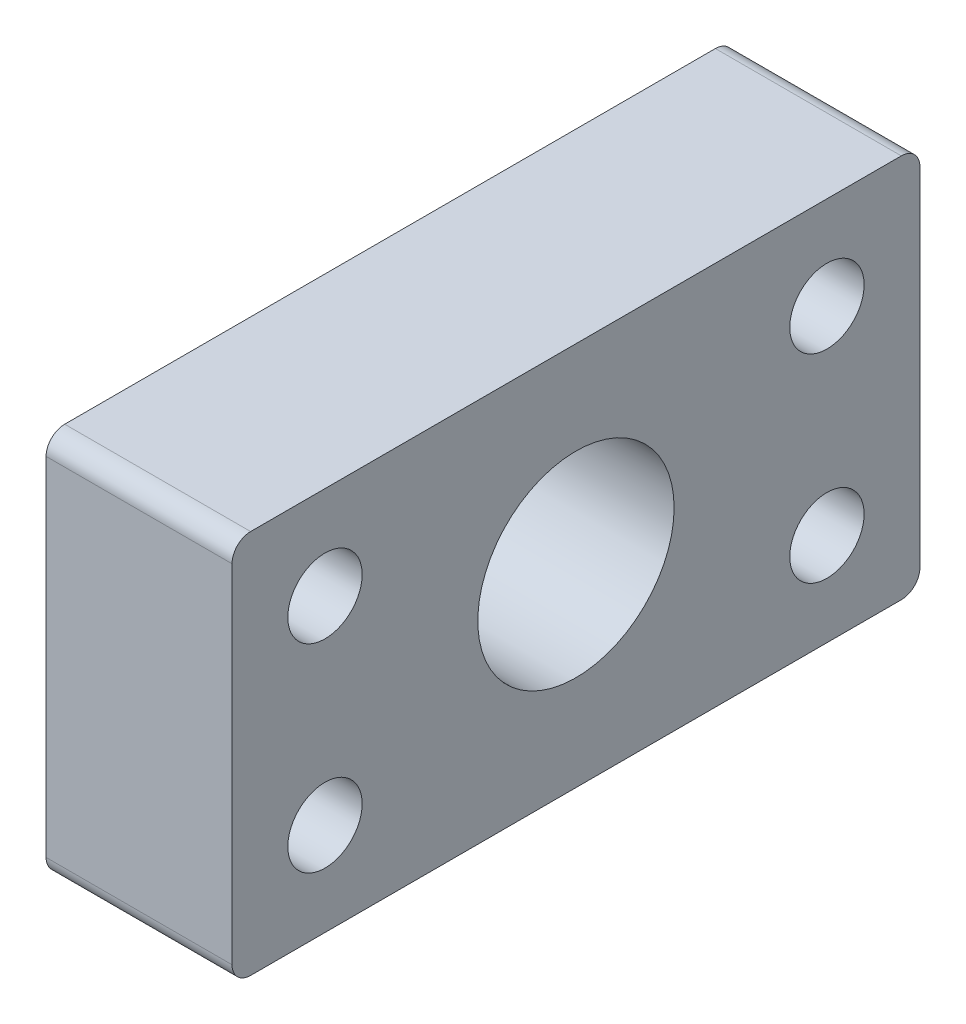
SolidWorks part; units mm, degrees
ref_plane "Спереди" through (0, 0, 0) normal (0, 0, 1) x (1, 0, 0)
ref_plane "Сверху" through (0, 0, 0) normal (0, 1, 0) x (1, 0, 0)
ref_plane "Справа" through (0, 0, 0) normal (1, 0, 0) x (0, 0, -1)
sketch "Эскиз1" plane through (0, 0, 0) normal (1, 0, 0) x (0, 0, -1)
  line L5 (-5, 10.68) -> (-5, 15.68)
  line L6 (-5, 15.68) -> (-5, 0)
  line L8 (27, -5) -> (-5, -5)
  line L9 (-5, -5) -> (-5, 0)
  line L10 (27, -5) -> (32, -5)
  line L11 (32, -5) -> (32, 15.68)
  line L12 (32, 15.68) -> (-5, 15.68)
  circle A0 centre (0, 10.68) radius 2
  circle A1 centre (27, 10.68) radius 2
  circle A2 centre (27, 0) radius 2
  circle A3 centre (0, 0) radius 2
  circle A4 centre (13.5, 5.3997) radius 5.2803
extrude "Бобышка-Вытянуть1" add sketch "Эскиз1" along normal blind 10 contours L11 L12 L5 L6 L9 L8 L10 A4 A3 A2 A1 A0
fillet "Скругление1" radius 1 4 edges at (5, -5, -32) (5, 15.68, -32) (5, -5, 5) (5, 15.68, 5)
